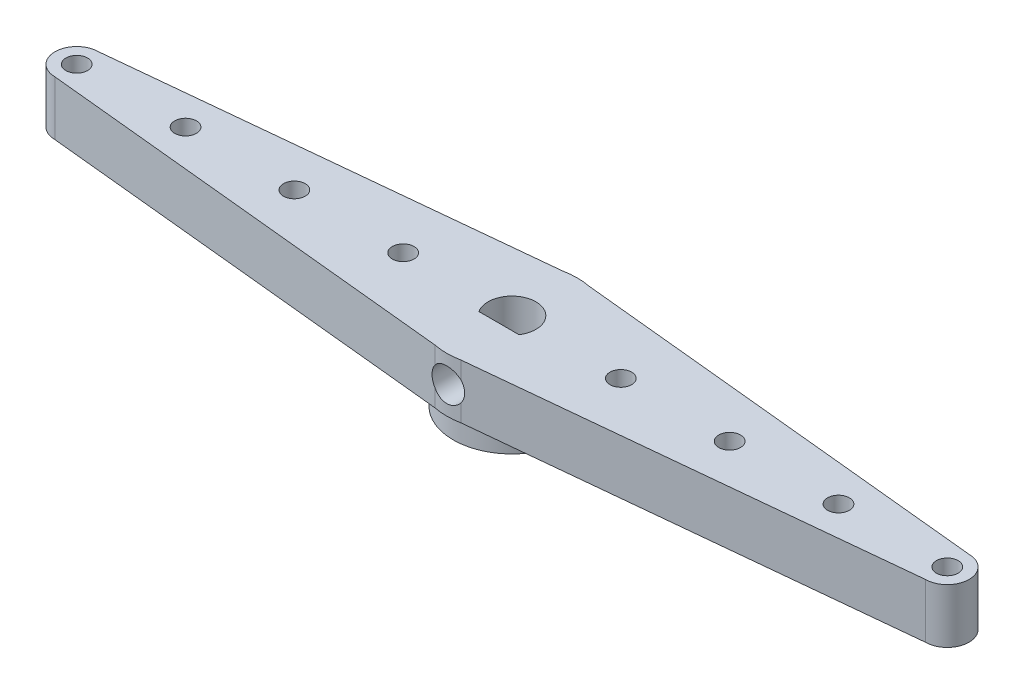
SolidWorks part; units mm, degrees
ref_plane "Front Plane" through (0, 0, 0) normal (0, 0, 1) x (1, 0, 0)
ref_plane "Top Plane" through (0, 0, 0) normal (0, 1, 0) x (1, 0, 0)
ref_plane "Right Plane" through (0, 0, 0) normal (1, 0, 0) x (0, 0, -1)
sketch "Sketch1" plane through (0, 0, 0) normal (0, 1, 0) x (1, 0, 0)
  line L0 (0.5941, 2.9406) -> (20, 1)
  line L1 (0.5941, -2.9406) -> (20, -1)
  line L2 (0, 0) -> (0, -9.861) construction
  line L3 (-0.5941, -2.9406) -> (-20, -1)
  line L4 (-0.5941, 2.9406) -> (-20, 1)
  line L5 (-0.866, -0.5) -> (0.866, -0.5) construction
  line L6 (0, -3) -> (-0.5941, -2.9406) construction
  line L7 (0, -3) -> (0.5941, -2.9406) construction
  line L8 (0, 3) -> (0.5941, 2.9406) construction
  line L9 (0, 3) -> (-0.5941, 2.9406) construction
  line L10 (-0.922, -0.6) -> (0.922, -0.6)
  arc A0 (0.5941, 2.9406) -> (-0.5941, 2.9406) centre (0, 0) ccw
  arc A1 (20, -1) -> (20, 1) centre (20, 0) ccw
  arc A2 (0.5941, -2.9406) -> (0.5941, 2.9406) centre (0, 0) ccw construction
  arc A3 (20, 1) -> (20, -1) centre (20, 0) ccw construction
  arc A4 (-20, 1) -> (-20, -1) centre (-20, 0) cw construction
  arc A5 (-20, -1) -> (-20, 1) centre (-20, 0) cw
  arc A6 (-0.5941, -2.9406) -> (0.5941, -2.9406) centre (0, 0) ccw
  arc A7 (-0.5941, 2.9406) -> (-0.5941, -2.9406) centre (0, 0) ccw construction
  arc A8 (0.866, -0.5) -> (-0.866, -0.5) centre (0, 0) ccw construction
  arc A9 (-0.866, -0.5) -> (0, -1) centre (0, 0) ccw construction
  arc A10 (0, -1) -> (0.866, -0.5) centre (0, 0) ccw construction
  circle A11 centre (5, 0) radius 0.5
  circle A12 centre (10, 0) radius 0.5
  circle A13 centre (15, 0) radius 0.5
  circle A14 centre (20, 0) radius 0.5
  circle A15 centre (-20, 0) radius 0.5
  circle A16 centre (-15, 0) radius 0.5
  circle A17 centre (-10, 0) radius 0.5
  circle A18 centre (-5, 0) radius 0.5
  arc A19 (0.922, -0.6) -> (-0.922, -0.6) centre (0, 0) ccw
  point P21 (0, -0.5)
  dimension "D1" = 6
  dimension "D2" = 2
  dimension "D4" = 2
  dimension "D6" = 1
  dimension "D3" = 20
  dimension "D5" = 0.5
  dimension "D7" = 5
  dimension "D9" = 0.1
  dimension "D8" = 4
extrude "Boss-Extrude1" add sketch "Sketch1" along normal blind 2.5
sketch "Sketch2" plane through (0, 0, 0) normal (0, 0, 1) x (1, 0, 0)
  line L0 (0, 2.5) -> (0, 0) construction
  line L1 (0.5941, 2.5) -> (-0.5941, 2.5) construction
  circle A0 centre (0, 1.25) radius 0.75
  point P2 (0, 0)
  point P4 (0, 1.25)
  dimension "D1" = 1.5
extrude "Cut-Extrude1" cut sketch "Sketch2" along normal blind 9
sketch "Sketch3" plane through (0, 0, 0) normal (0, 1, 0) x (1, 0, 0)
  circle A0 centre (0, 0) radius 2
  circle A1 centre (0, 0) radius 2.7
  point P2 (0, 0)
  dimension "D1" = 4
  dimension "D2" = 0.7
extrude "Boss-Extrude2" add sketch "Sketch3" against normal blind 1.1
